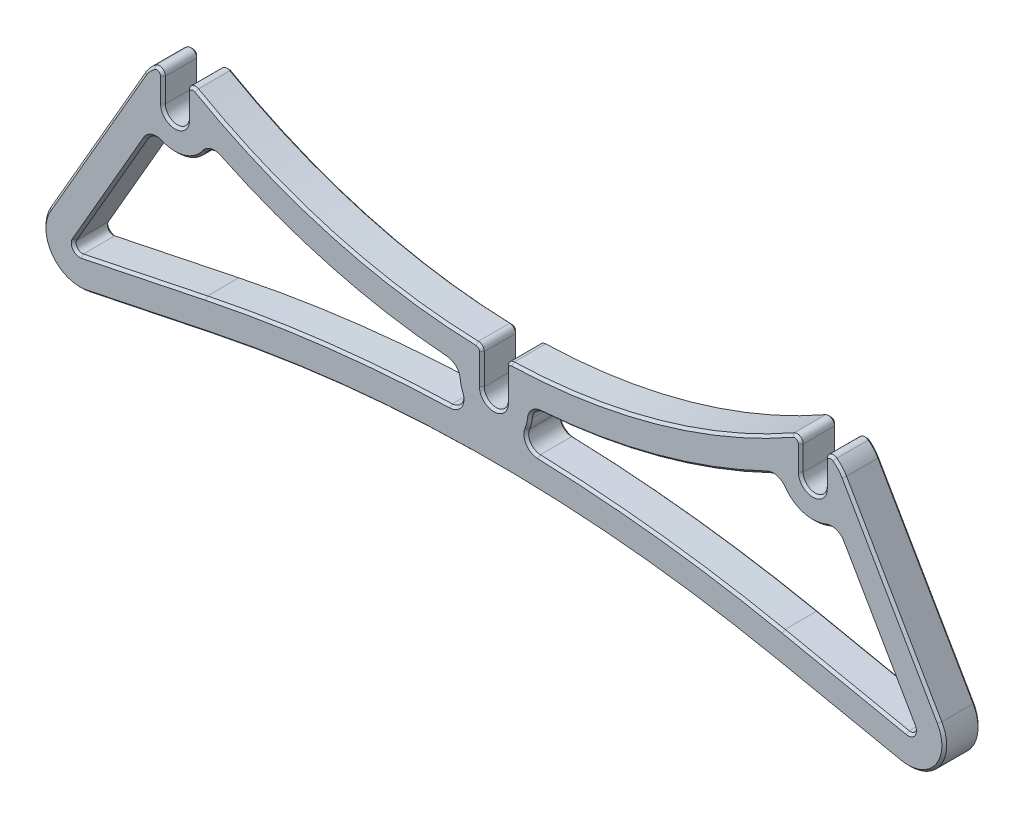
SolidWorks part; units mm, degrees
ref_plane "Front Plane" through (0, 0, 0) normal (0, 0, 1) x (1, 0, 0)
ref_plane "Top Plane" through (0, 0, 0) normal (0, 1, 0) x (1, 0, 0)
ref_plane "Right Plane" through (0, 0, 0) normal (1, 0, 0) x (0, 0, -1)
sketch "Sketch1" plane through (0, 0, 0) normal (0, 0, 1) x (1, 0, 0)
  line L0 (0, 0) -> (-95.2628, -55) construction
  line L1 (0, 0) -> (0, -110) construction
  line L2 (0, 0) -> (-55, -95.2628) construction
  line L3 (-55, -95.2628) -> (-71.7047, -124.1962) construction
  line L4 (-67.4872, -124.8752) -> (-46.8941, -120.6078)
  line L5 (-73.9008, -116) -> (-58.0962, -88.6255)
  line L6 (0, 0) -> (-52.9, -91.6255) construction
  line L7 (0, 0) -> (0, -105.8) construction
  line L8 (-68.7047, -125) -> (0, -125) construction
  line L9 (0, -110) -> (0, -346.9026) construction
  line L10 (-52.9, -91.6255) -> (-58.0962, -88.6255) construction
  line L11 (0, -346.9026) -> (-52.9, -91.6255) construction
  line L12 (73.9008, -116) -> (58.0962, -88.6255)
  line L13 (67.4872, -124.8752) -> (46.8941, -120.6078)
  line L14 (-73.9008, -116) -> (-68.7047, -119) construction
  line L15 (-67.4872, -124.8752) -> (-68.7047, -119) construction
  line L16 (-69.5707, -118.5) -> (-57.7347, -97.9994)
  line L19 (-68.5018, -119.9792) -> (-47.9087, -115.7118)
  line L20 (69.5707, -118.5) -> (57.7347, -97.9994)
  line L21 (68.5018, -119.9792) -> (47.9087, -115.7118)
  circle A0 centre (0, 0) radius 110 construction
  circle A1 centre (-52.9, -91.6255) radius 2
  arc A2 (-73.9008, -116) -> (-67.4872, -124.8752) centre (-68.7047, -119) ccw
  circle A3 centre (0, -105.8) radius 2
  circle A4 centre (52.9, -91.6255) radius 2
  arc A5 (-46.8941, -120.6078) -> (46.8941, -120.6078) centre (0, -346.9026) cw
  arc A6 (-58.0962, -88.6255) -> (-49.9, -86.4293) centre (-52.9, -91.6255) cw
  arc A7 (-49.9, -86.4293) -> (49.9, -86.4293) centre (0, 0) ccw
  arc A8 (58.0962, -88.6255) -> (49.9, -86.4293) centre (52.9, -91.6255) ccw
  arc A9 (73.9008, -116) -> (67.4872, -124.8752) centre (68.7047, -119) cw
  arc A11 (-69.5707, -118.5) -> (-68.5018, -119.9792) centre (-68.7047, -119) ccw
  arc A14 (-47.9087, -115.7118) -> (-7.3071, -110.9131) centre (0, -346.9026) cw
  arc A15 (-7.8199, -104.5078) -> (-45.4817, -94.4164) centre (0, 0) cw
  arc A16 (-55.227, -97.1559) -> (-47.9873, -95.07) centre (-52.9, -91.6255) ccw
  arc A18 (-5.9768, -106.3267) -> (-5.5268, -108.1355) centre (0, -105.8) ccw
  arc A19 (-7.3071, -110.9131) -> (-5.5268, -108.1355) centre (-7.369, -108.9141) ccw
  arc A20 (-5.9768, -106.3267) -> (-7.8199, -104.5078) centre (-7.9691, -106.5023) ccw
  arc A21 (-45.4817, -94.4164) -> (-47.9873, -95.07) centre (-46.3497, -96.2182) ccw
  arc A22 (-57.7347, -97.9994) -> (-55.227, -97.1559) centre (-56.0026, -98.9994) cw
  arc A23 (47.9087, -115.7118) -> (7.3071, -110.9131) centre (0, -346.9026) ccw
  arc A24 (7.3071, -110.9131) -> (5.5268, -108.1355) centre (7.369, -108.9141) cw
  arc A25 (5.9768, -106.3267) -> (5.5268, -108.1355) centre (0, -105.8) cw
  arc A26 (5.9768, -106.3267) -> (7.8199, -104.5078) centre (7.9691, -106.5023) cw
  arc A27 (7.8199, -104.5078) -> (45.4817, -94.4164) centre (0, 0) ccw
  arc A28 (45.4817, -94.4164) -> (47.9873, -95.07) centre (46.3497, -96.2182) cw
  arc A29 (55.227, -97.1559) -> (47.9873, -95.07) centre (52.9, -91.6255) cw
  arc A30 (57.7347, -97.9994) -> (55.227, -97.1559) centre (56.0026, -98.9994) ccw
  arc A31 (69.5707, -118.5) -> (68.5018, -119.9792) centre (68.7047, -119) cw
  point P31 (0, -115.8)
  dimension "D1" = 220
  dimension "D4" = 4
  dimension "D10" = 1
  dimension "D12" = 2
  dimension "D2" = 60
  dimension "D5" = 105.8
  dimension "D8" = 30
  dimension "D9" = 15
  dimension "D3" = 10
  dimension "D11" = 5
  dimension "D6" = 5
  dimension "D7" = 3
extrude "Boss-Extrude1" add sketch "Sketch1" along normal blind 6
sketch "Sketch2" plane through (0, 0, 6) normal (0, 0, 1) x (1, 0, 0)
  line L0 (-54.9, -91.6255) -> (-54.9, -83.6255)
  line L1 (-54.9, -83.6255) -> (-50.9, -83.6255)
  line L2 (-50.9, -83.6255) -> (-50.9, -91.6255)
  line L3 (-54.9, -91.6255) -> (-50.9, -91.6255)
  line L4 (0, -105.8) -> (0, -94.3455) construction
  line L5 (-2, -105.8) -> (2, -105.8)
  line L6 (-2, -105.8) -> (-2, -97.8)
  line L7 (-2, -97.8) -> (2, -97.8)
  line L8 (2, -105.8) -> (2, -97.8)
  line L9 (54.9, -91.6255) -> (50.9, -91.6255)
  line L10 (50.9, -83.6255) -> (50.9, -91.6255)
  line L11 (54.9, -83.6255) -> (50.9, -83.6255)
  line L12 (54.9, -91.6255) -> (54.9, -83.6255)
  circle A0 centre (-52.9, -91.6255) radius 2 construction
  circle A1 centre (-52.9, -91.6255) radius 2 construction
  circle A2 centre (0, -105.8) radius 2 construction
  circle A3 centre (0, -105.8) radius 2 construction
  dimension "D1" = 8
  dimension "D2" = 8
extrude "Cut-Extrude1" cut sketch "Sketch2" against normal through all both and the other way through all
fillet "Fillet1" radius 1 6 edges at (-2, -99.78, 3) (2, -99.78, 3) (50.9, -85.9686, 3) (54.9, -85.9686, 3) (-54.9, -85.9686, 3) (-50.9, -85.9686, 3)
chamfer "Chamfer1" distance 0.4 angle 45 96 edges at (5.6852, -109.9933, 0) (5.8225, -107.2487, 0) (6.5643, -105.0787, 0) (27.1242, -101.229, 0) (46.8545, -94.283, 0) (51.2389, -97.391, 0) (56.6402, -97.1037, 0) (63.6527, -108.2497, 0) (69.5152, -119.5857, 0) (58.2052, -117.8455, 0) (27.712, -112.432, 0) (52.9, -93.6255, 0) (0, -107.8, 0) (-52.9, -93.6255, 0) (-57.1907, -122.7415, 0) (0, -115.8, 0) (57.1907, -122.7415, 0) (73.5678, -122.5143, 0) (65.9985, -102.3127, 0) (57.3892, -87.6447, 0) (-26.9874, -96.0819, 0) (26.9874, -96.0819, 0) (-57.3892, -87.6447, 0) (-65.9985, -102.3127, 0) (-73.5678, -122.5143, 0) (-63.6527, -108.2497, 0) (-56.6402, -97.1037, 0) (-51.2389, -97.391, 0) (-46.8545, -94.283, 0) (-27.1242, -101.229, 0) (-6.5643, -105.0787, 0) (-5.8225, -107.2487, 0) (-5.6852, -109.9933, 0) (-27.712, -112.432, 0) (-58.2052, -117.8455, 0) (-69.5152, -119.5857, 0) (69.5152, -119.5857, 6) (63.6527, -108.2497, 6) (56.6402, -97.1037, 6) (51.2389, -97.391, 6) (46.8545, -94.283, 6) (27.1242, -101.229, 6) (6.5643, -105.0787, 6) (5.8225, -107.2487, 6) (5.6852, -109.9933, 6) (27.712, -112.432, 6) (58.2052, -117.8455, 6) (-27.712, -112.432, 6) (-5.6852, -109.9933, 6) (-5.8225, -107.2487, 6) (-6.5643, -105.0787, 6) (-27.1242, -101.229, 6) (-46.8545, -94.283, 6) (-51.2389, -97.391, 6) (-56.6402, -97.1037, 6) (-63.6527, -108.2497, 6) (-69.5152, -119.5857, 6) (-58.2052, -117.8455, 6) (-65.9985, -102.3127, 6) (-57.3892, -87.6447, 6) (-26.9874, -96.0819, 6) (26.9874, -96.0819, 6) (57.3892, -87.6447, 6) (65.9985, -102.3127, 6) (73.5678, -122.5143, 6) (57.1907, -122.7415, 6) (0, -115.8, 6) (-57.1907, -122.7415, 6) (-73.5678, -122.5143, 6) (-50.4025, -86.7175, 0) (-50.9, -89.6038, 0) (-54.9, -89.6255, 0) (-55.4528, -86.7311, 0) (55.4528, -86.7311, 0) (54.9, -89.6255, 0) (50.9, -89.6038, 0) (50.4025, -86.7175, 0) (2.2824, -100.0588, 0) (2, -103.2777, 0) (-2, -103.2777, 0) (-2.2824, -100.0588, 0) (2.2824, -100.0588, 6) (50.4025, -86.7175, 6) (55.4528, -86.7311, 6) (-55.4528, -86.7311, 6) (-50.4025, -86.7175, 6) (-2.2824, -100.0588, 6)
equation "\"D11@Sketch1\"=\"D6@Sketch1\""
equation "\"D2@Sketch2\"=\"D1@Sketch2\""
